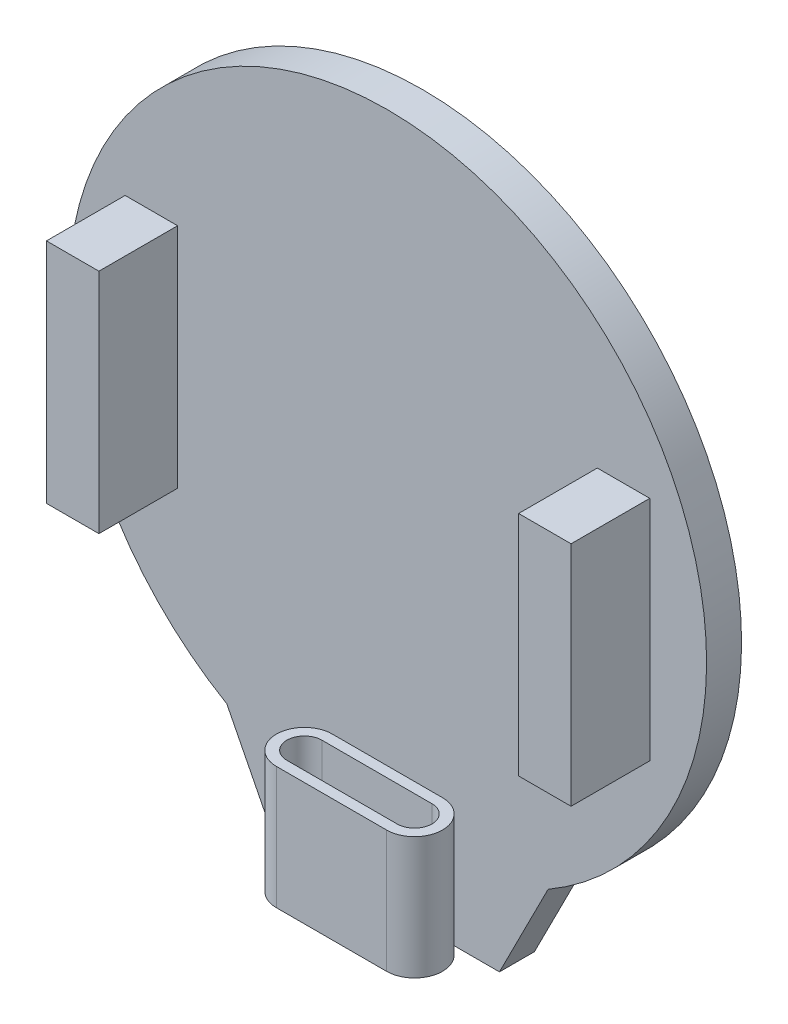
SolidWorks part; units mm, degrees
ref_plane "前视基准面" through (0, 0, 0) normal (0, 0, 1) x (1, 0, 0)
ref_plane "上视基准面" through (0, 0, 0) normal (0, 1, 0) x (1, 0, 0)
ref_plane "右视基准面" through (0, 0, 0) normal (1, 0, 0) x (0, 0, -1)
sketch "草图1" plane through (0, 0, 0) normal (0, 0, 1) x (1, 0, 0)
  line L0 (-9.185, -15.7702) -> (9.185, -15.7702) construction
  line L1 (-6.405, -21.2502) -> (6.405, -21.2502)
  line L2 (-9.185, -15.7702) -> (-6.405, -21.2502)
  line L3 (6.405, -21.2502) -> (9.185, -15.7702)
  arc A0 (9.185, -15.7702) -> (-9.185, -15.7702) centre (0, 0) ccw
  point P7 (0, -21.2502)
  point P8 (0, -15.7702)
  dimension "D1" = 36.5
  dimension "D2" = 18.37
  dimension "D3" = 12.81
  dimension "D4" = 5.48
extrude "凸台-拉伸1" add sketch "草图1" along normal blind 2
sketch "草图2" plane through (0, 0, 0) normal (0, 0, -1) x (-1, 0, 0)
  circle A0 centre (0, 0) radius 16.2
  dimension "D1" = 32.4
extrude "凸台-拉伸2" add sketch "草图2" along normal blind 1.4
sketch "草图3" plane through (0, 0, 2) normal (0, 0, 1) x (1, 0, 0)
  line L0 (0, 0) -> (0, -21.2502) construction
  line L1 (-6.405, -21.2502) -> (6.405, -21.2502) construction
  line L2 (-13.5, 6.5) -> (-13.5, -6.5) construction
  line L3 (-15, 6.5) -> (-12, 6.5)
  line L4 (-15, 6.5) -> (-15, -6.5)
  line L5 (-15, -6.5) -> (-12, -6.5)
  line L6 (-12, 6.5) -> (-12, -6.5)
  line L7 (15, -6.5) -> (12, -6.5)
  line L8 (12, 6.5) -> (12, -6.5)
  line L9 (15, 6.5) -> (12, 6.5)
  line L10 (15, 6.5) -> (15, -6.5)
  point P11 (-13.5, 0)
  dimension "D1" = 13
  dimension "D2" = 3
  dimension "D3" = 13.5
extrude "凸台-拉伸3" add sketch "草图3" along normal blind 4.5
sketch "草图4" plane through (0, -21.2502, 0) normal (0, -1, 0) x (1, 0, 0)
  line L0 (-3.15, 3.6) -> (3.15, 3.6) construction
  line L1 (-3.15, 5.2) -> (3.15, 5.2)
  line L2 (-3.15, 2) -> (3.15, 2)
  line L3 (-6.405, 2) -> (6.405, 2) construction
  line L4 (-3.15, 3.6) -> (3.15, 3.6) construction
  line L5 (-3.15, 4.6) -> (3.15, 4.6)
  line L6 (-3.15, 2.6) -> (3.15, 2.6)
  arc A0 (-3.15, 5.2) -> (-3.15, 2) centre (-3.15, 3.6) ccw
  arc A1 (3.15, 2) -> (3.15, 5.2) centre (3.15, 3.6) ccw
  arc A2 (-3.15, 4.6) -> (-3.15, 2.6) centre (-3.15, 3.6) ccw
  arc A3 (3.15, 2.6) -> (3.15, 4.6) centre (3.15, 3.6) ccw
  point P2 (0, 3.6)
  point P7 (0, 3.6)
  dimension "D1" = 6.3
  dimension "D2" = 3.2
  dimension "D3" = 1.6
  dimension "D4" = 2
extrude "凸台-拉伸4" add sketch "草图4" against normal blind 7
